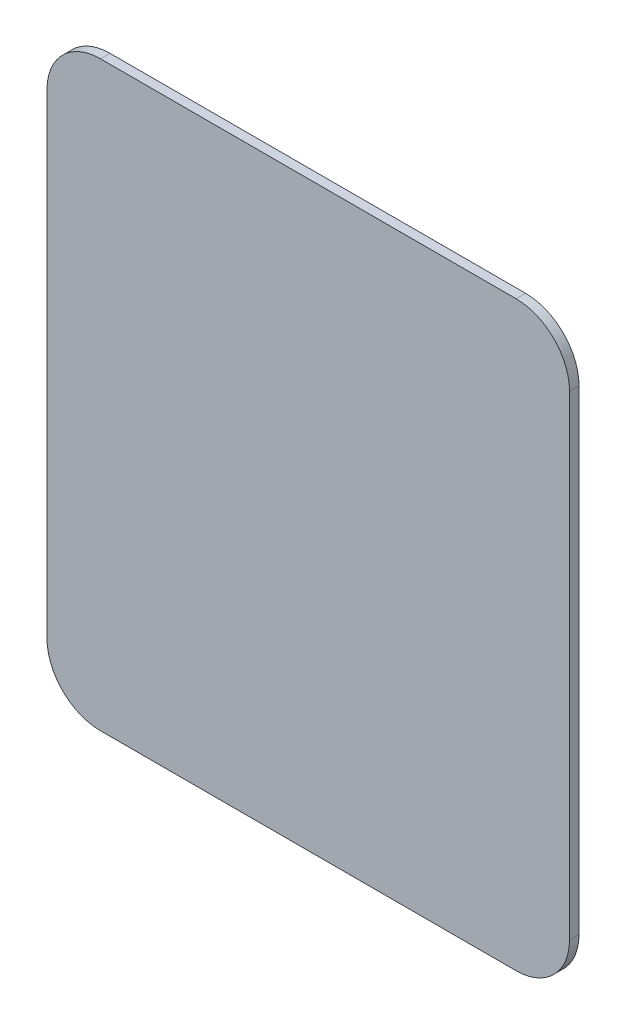
SolidWorks part; units mm, degrees
ref_plane "Front Plane" through (0, 0, 0) normal (0, 0, 1) x (1, 0, 0)
ref_plane "Top Plane" through (0, 0, 0) normal (0, 1, 0) x (1, 0, 0)
ref_plane "Right Plane" through (0, 0, 0) normal (1, 0, 0) x (0, 0, -1)
sketch "Sketch1" plane through (0, 0, 0) normal (0, 0, 1) x (1, 0, 0)
  line L1 (-120.4727, 50.2826) -> (-32.4727, 50.2826)
  line L2 (-120.4727, 50.2826) -> (-120.4727, -47.7174)
  line L3 (-120.4727, -47.7174) -> (-32.4727, -47.7174)
  line L4 (-32.4727, 50.2826) -> (-32.4727, -47.7174)
  point P4 (-120.4727, 50.2826)
  dimension "D1" = 88
  dimension "D2" = 98
extrude "Boss-Extrude1" add sketch "Sketch1" along normal blind 1.6
fillet "Fillet1" radius 9 4 edges at (-120.4727, 50.2826, 0.8) (-120.4727, -47.7174, 0.8) (-32.4727, -47.7174, 0.8) (-32.4727, 50.2826, 0.8)
